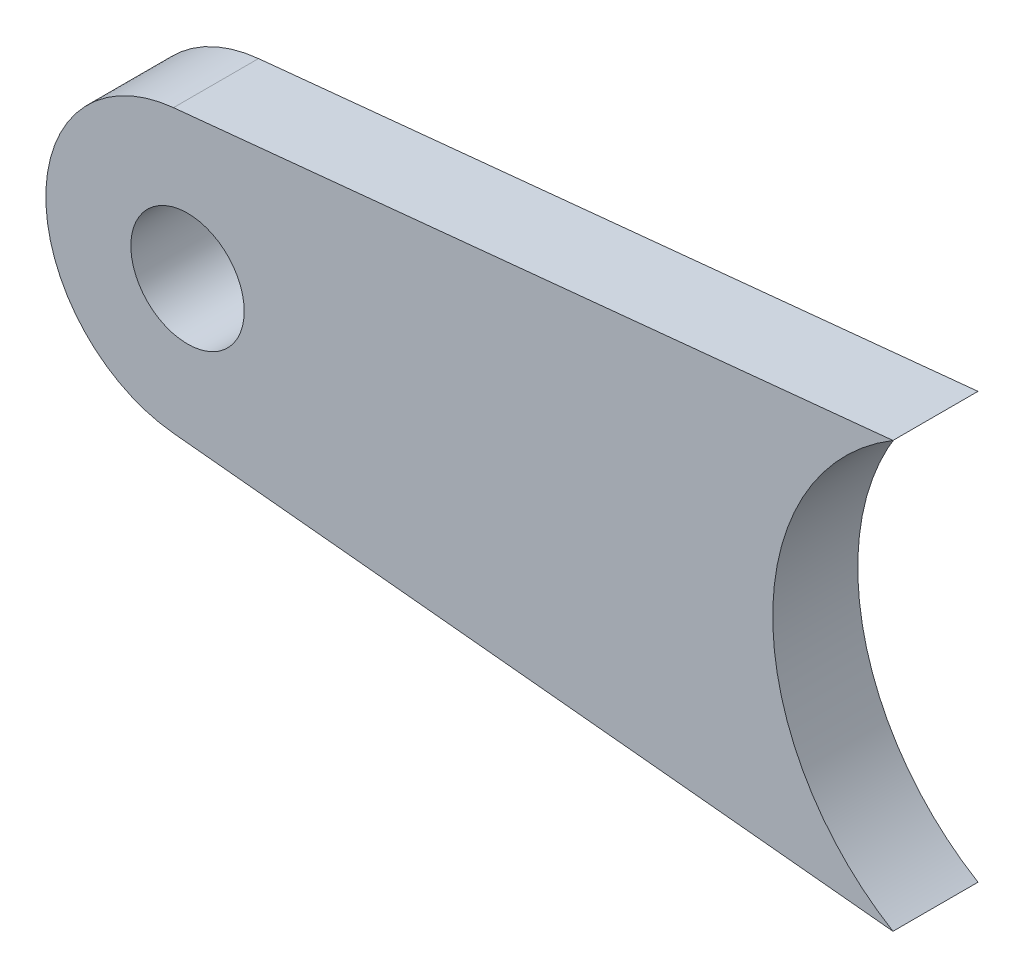
SolidWorks part; units mm, degrees
material "ASTM A36 Steel"
ref_plane "Front Plane" through (0, 0, 0) normal (0, 0, 1) x (1, 0, 0)
ref_plane "Top Plane" through (0, 0, 0) normal (0, 1, 0) x (1, 0, 0)
ref_plane "Right Plane" through (0, 0, 0) normal (1, 0, 0) x (0, 0, -1)
sketch "Sketch1" plane through (0, 0, 0) normal (0, 0, 1) x (1, 0, 0)
  line L4 (93.1141, 107.1269) -> (-8.4372, 97.0288)
  line L5 (-8.4372, 57.2251) -> (93.1141, 47.1269)
  arc A4 (-8.4372, 97.0288) -> (-8.4372, 57.2251) centre (-6.4581, 77.1269) ccw
  arc A5 (93.1141, 107.1269) -> (93.1141, 47.1269) centre (111.1419, 77.1269) ccw
  circle A6 centre (-6.4581, 77.1269) radius 8
  dimension "D1" = 20
  dimension "D2" = 60
  dimension "D3" = 16
extrude "Boss-Extrude1" add sketch "Sketch1" along normal mid plane 12
